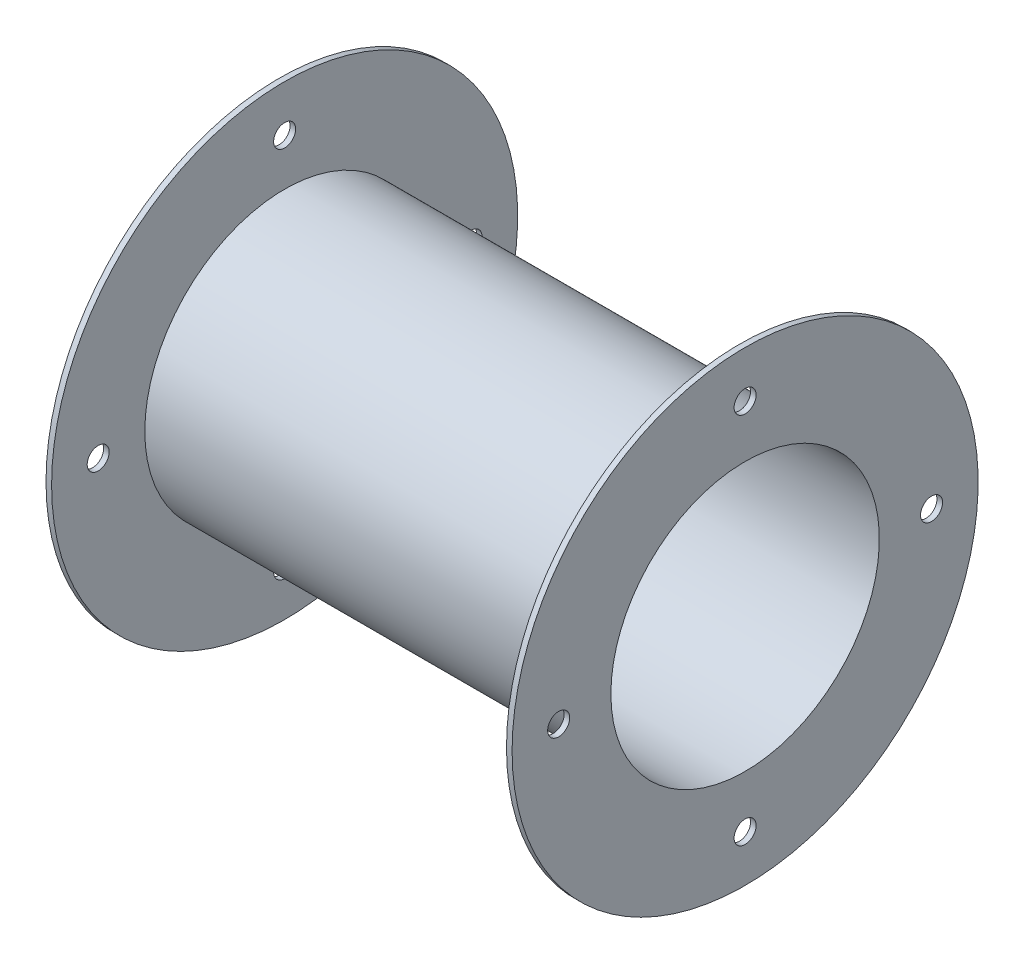
SolidWorks part; units mm, degrees
material "201 Annealed Stainless Steel (SS)"
ref_plane "Front Plane" through (0, 0, 0) normal (0, 0, 1) x (1, 0, 0)
ref_plane "Top Plane" through (0, 0, 0) normal (0, 1, 0) x (1, 0, 0)
ref_plane "Right Plane" through (0, 0, 0) normal (1, 0, 0) x (0, 0, -1)
sketch "Sketch3" plane through (0, 0, 0) normal (0, 0, 1) x (1, 0, 0)
  line L0 (0, 0) -> (0, 26.924)
  line L1 (0, 26.924) -> (1.524, 26.924)
  line L2 (1.524, 26.924) -> (1.524, 1.524)
  line L3 (1.524, 1.524) -> (125.476, 1.524)
  line L4 (125.476, 1.524) -> (125.476, 26.924)
  line L5 (125.476, 26.924) -> (127, 26.924)
  line L6 (127, 26.924) -> (127, 0)
  line L7 (127, 0) -> (0, 0)
  line L8 (-7.3746, -36.576) -> (91.6555, -36.576) construction
  dimension "D1" = 36.576
  dimension "D2" = 63.5
  dimension "D3" = 1.524
  dimension "D4" = 1.524
  dimension "D5" = 127
revolve "Revolve1" add sketch "Sketch3" angle 360 about L8
sketch "Sketch4" plane through (0, 0, 0) normal (-1, 0, 0) x (0, 0, 1)
  circle A0 centre (0, 14.224) radius 3
  dimension "D1" = 6
  dimension "D2" = 50.8
extrude "Cut-Extrude1" cut sketch "Sketch4" against normal through all both and the other way through all
pattern_circular "CirPattern1" count 4 over 360 about axis through (0, -36.576, 0) along (1, 0, 0) of "Cut-Extrude1"
